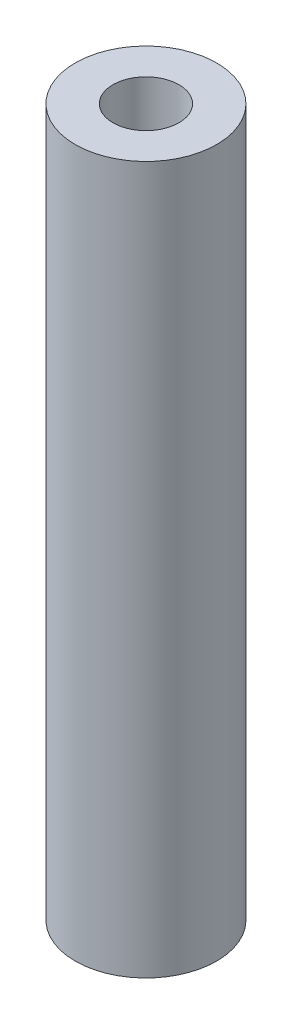
SolidWorks part; units mm, degrees
ref_plane "Front Plane" through (0, 0, 0) normal (0, 0, 1) x (1, 0, 0)
ref_plane "Top Plane" through (0, 0, 0) normal (0, 1, 0) x (1, 0, 0)
ref_plane "Right Plane" through (0, 0, 0) normal (1, 0, 0) x (0, 0, -1)
sketch "Sketch1" plane through (0, 0, 0) normal (0, 1, 0) x (1, 0, 0)
  circle A0 centre (0, 0) radius 3
  circle A1 centre (0, 0) radius 1.4
  dimension "D1" = 2.8
  dimension "D2" = 6
extrude "Extrusion" add sketch "Sketch1" along normal blind 30
